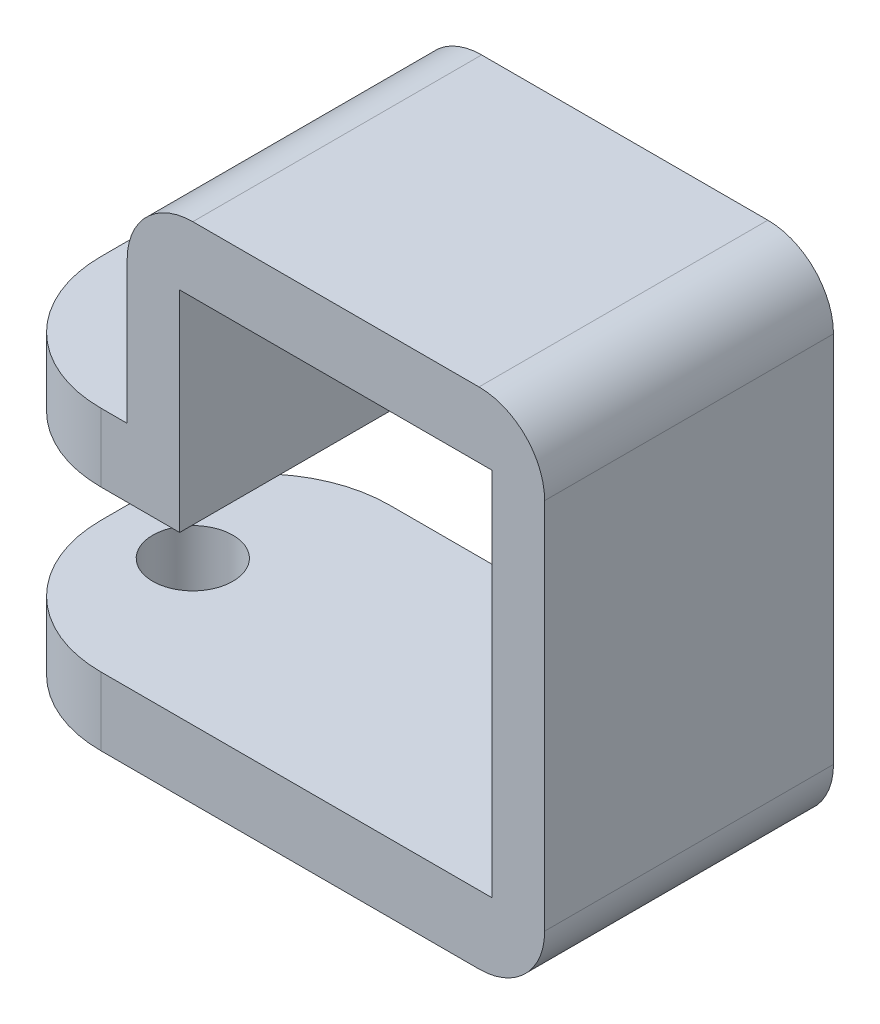
SolidWorks part; units mm, degrees
ref_plane "Front Plane" through (0, 0, 0) normal (0, 0, 1) x (1, 0, 0)
ref_plane "Top Plane" through (0, 0, 0) normal (0, 1, 0) x (1, 0, 0)
ref_plane "Right Plane" through (0, 0, 0) normal (1, 0, 0) x (0, 0, -1)
sketch "Sketch1" plane through (0, 0, 0) normal (0, 0, 1) x (1, 0, 0)
  line L0 (0, 0) -> (0, 8) construction
  line L1 (-5.95, 0) -> (-5.95, 8)
  line L2 (-5.95, 8) -> (5.95, 8)
  line L4 (7.95, 10.5) -> (-7.95, 10.5)
  line L5 (-7.95, 10.5) -> (-7.95, 2.6)
  line L6 (-8.6587, 0) -> (-5.95, 0)
  line L8 (-8.6587, 0) -> (-13.95, 0)
  line L10 (-7.95, 2.6) -> (-13.95, 2.6)
  line L11 (-13.95, 0) -> (-13.95, 2.6)
  line L15 (7.95, 10.5) -> (7.95, 2.6)
  line L16 (5.95, 0) -> (5.95, 8)
  line L17 (0, 10.5) -> (0, 11.3048) construction
  line L18 (5.95, 0) -> (5.95, -6.1)
  line L19 (5.95, -6.1) -> (-13.95, -6.1)
  line L20 (-13.95, -6.1) -> (-13.95, -8.7)
  line L21 (-13.95, -8.7) -> (7.95, -8.7)
  line L22 (7.95, -8.7) -> (7.95, 2.6)
  dimension "D1" = 5.95
  dimension "D2" = 8
  dimension "D3" = 2.5
  dimension "D4" = 2
  dimension "D5" = 2.6
  dimension "D6" = 6
  dimension "D7" = 6.1
  dimension "D8" = 2.6
extrude "Boss-Extrude1" add sketch "Sketch1" along normal blind 11
fillet "Fillet2" radius 2.5 3 edges at (7.95, 10.5, 5.5) (-7.95, 10.5, 5.5) (7.95, -8.7, 5.5)
sketch "Sketch2" plane through (0, 2.6, 0) normal (0, 1, 0) x (1, 0, 0)
  line L0 (-13.95, -11) -> (-13.95, 0) construction
  circle A0 centre (-10.95, -5.5) radius 1.525
  dimension "D2" = 3.05
  dimension "D1" = 3
extrude "Cut-Extrude1" cut sketch "Sketch2" against normal through all
fillet "Fillet3" radius 5 4 edges at (-13.95, -7.4, 0) (-13.95, -7.4, 11) (-13.95, 1.3, 11) (-13.95, 1.3, 0)
